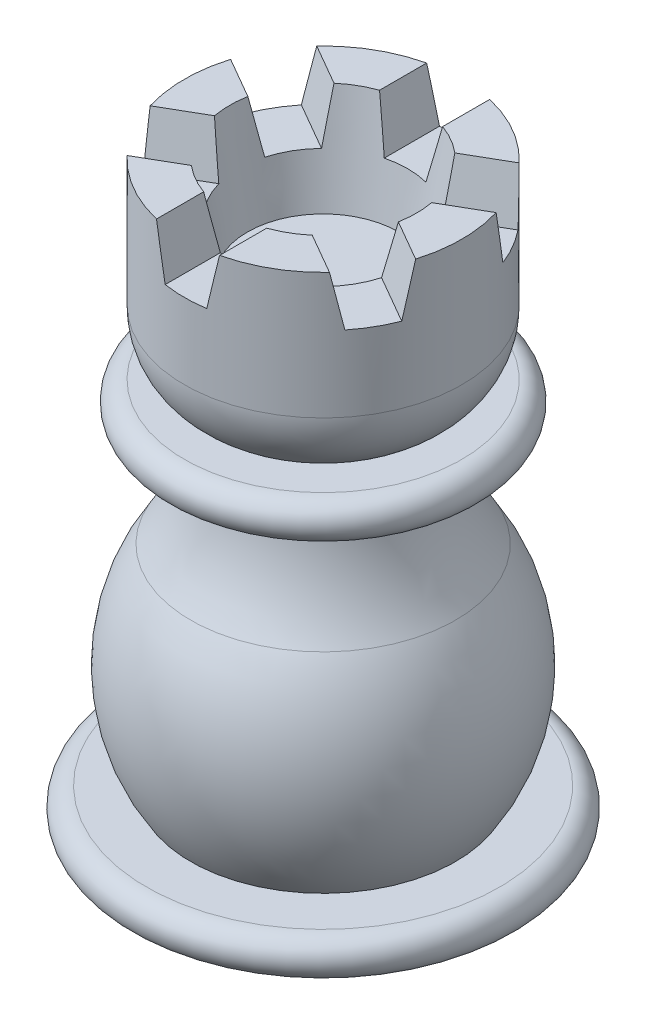
SolidWorks part; units mm, degrees
ref_plane "Front Plane" through (0, 0, 0) normal (0, 0, 1) x (1, 0, 0)
ref_plane "Top Plane" through (0, 0, 0) normal (0, 1, 0) x (1, 0, 0)
ref_plane "Right Plane" through (0, 0, 0) normal (1, 0, 0) x (0, 0, -1)
sketch "Sketch1" plane through (0, 0, 0) normal (0, 0, 1) x (1, 0, 0)
  line L0 (0, 0) -> (14, 0)
  line L1 (14, 3) -> (10.5, 3)
  line L2 (8, 27.8747) -> (11, 27.8747)
  line L3 (11, 30.8747) -> (8.1195, 30.8747)
  line L5 (11, 46) -> (7.4106, 46)
  line L6 (7.4106, 46) -> (6, 38)
  line L7 (6, 38) -> (0, 38)
  line L8 (0, 0) -> (0, 68.8293) construction
  line L9 (0, 38) -> (0, 0)
  line L10 (11, 46) -> (11, 36)
  arc A0 (14, 0) -> (14, 3) centre (14, 1.5) ccw
  arc A1 (11, 27.8747) -> (11, 30.8747) centre (11, 29.3747) ccw
  arc A3 (10.5, 3) -> (10.5, 19.5831) centre (-2, 11.2916) ccw
  arc A4 (10.5, 19.5831) -> (8, 27.8747) centre (23, 27.8747) cw
  arc A7 (11, 36) -> (8.1195, 30.8747) centre (5, 36) cw
  point P9 (13, 11.2916)
  point P12 (12.5861, 34.2079)
  point P21 (10.1152, 33.749)
  point P22 (5.0662, 36)
  point P24 (5.0298, 36)
  dimension "D3" = 1.5
  dimension "D5" = 2
  dimension "D6" = 8
  dimension "D8" = 22
  dimension "D13" = 13
  dimension "D9" = 15
  dimension "D14" = 15
  dimension "D4" = 1.5
  dimension "D7" = 6
  dimension "D1" = 28
  dimension "D2" = 21
  dimension "D10" = 16
  dimension "D11" = 10
  dimension "D12" = 12
  dimension "D15" = 46
revolve "Revolve1" add sketch "Sketch1" angle 360 about L8
sketch "Sketch2" plane through (0, 0, 0) normal (0, 0, 1) x (1, 0, 0)
  line L0 (-2.5002, 46) -> (-1.65, 42)
  line L1 (7.4106, 46) -> (-7.4106, 46) construction
  line L2 (-1.65, 42) -> (1.6495, 42)
  line L3 (1.6495, 42) -> (2.4998, 46)
  line L4 (0, 0) -> (0, 80.614) construction
  line L5 (-14, 0) -> (14, 0) construction
  dimension "D1" = 24
  dimension "D2" = 12
  dimension "D3" = 5
  dimension "D4" = 4
  dimension "D5" = 3.2995
  dimension "D6" = 1.65
extrude "Cut-Extrude1" cut sketch "Sketch2" against normal through all both and the other way through all
pattern_circular "CirPattern1" count 3 over 360 of "Cut-Extrude1"
